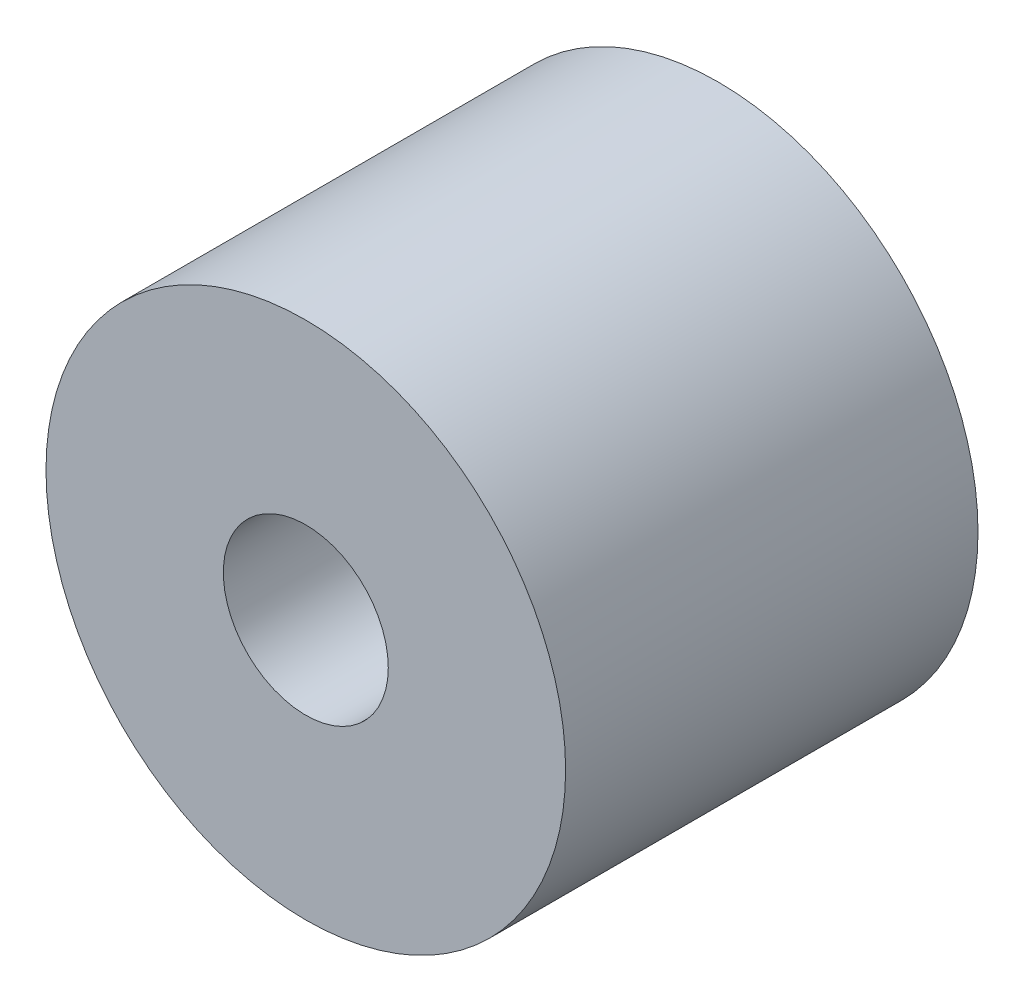
SolidWorks part; units mm, degrees
ref_plane "Front Plane" through (0, 0, 0) normal (0, 0, 1) x (1, 0, 0)
ref_plane "Top Plane" through (0, 0, 0) normal (0, 1, 0) x (1, 0, 0)
ref_plane "Right Plane" through (0, 0, 0) normal (1, 0, 0) x (0, 0, -1)
sketch "Sketch1" plane through (0, 0, 0) normal (0, 0, 1) x (1, 0, 0)
  circle A0 centre (0, 0) radius 15.75
  circle A1 centre (0, 0) radius 5
  dimension "D1" = 31.5
  dimension "D2" = 10
extrude "Boss-Extrude1" add sketch "Sketch1" along normal blind 25
sketch "Sketch2" plane through (0, 0, 0) normal (0, 1, 0) x (1, 0, 0)
  line L0 (0, 0) -> (0, -25) construction
  line L1 (-15.75, -25) -> (15.75, -25) construction
